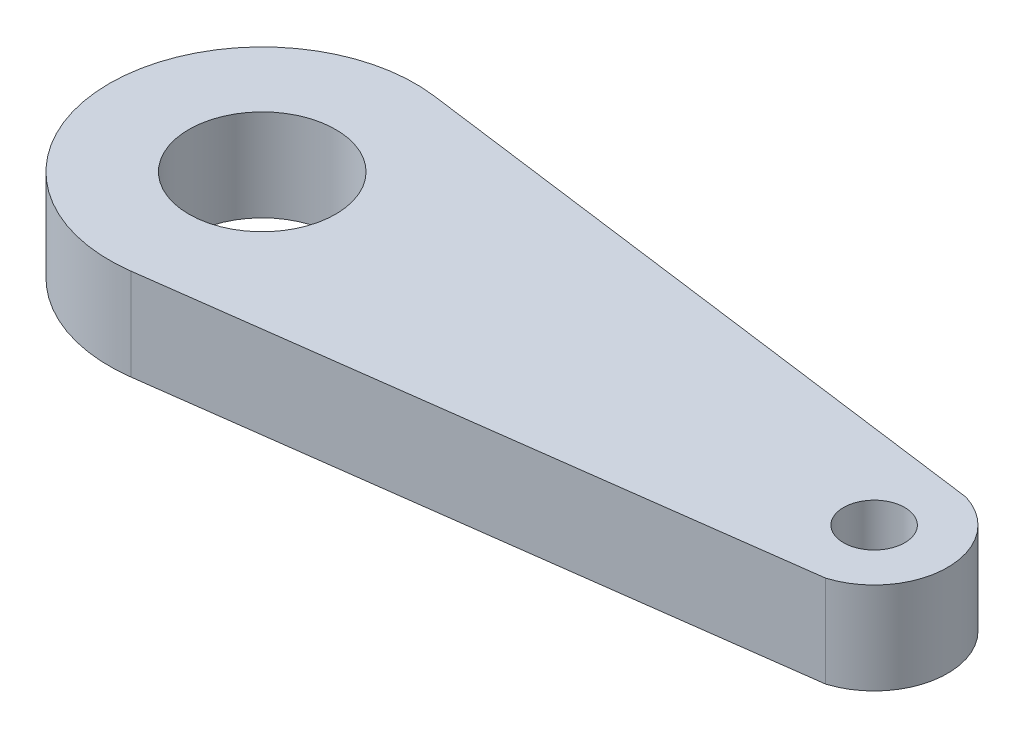
SolidWorks part; units mm, degrees
ref_plane "Front Plane" through (0, 0, 0) normal (0, 0, 1) x (1, 0, 0)
ref_plane "Top Plane" through (0, 0, 0) normal (0, 1, 0) x (1, 0, 0)
ref_plane "Right Plane" through (0, 0, 0) normal (1, 0, 0) x (0, 0, -1)
sketch "Sketch1" plane through (0, 0, 0) normal (0, 1, 0) x (1, 0, 0)
  line L0 (-565.5094, 314.7358) -> (707.5748, 145.6391)
  line L2 (-565.5094, -314.7358) -> (707.5748, -145.6391)
  arc A0 (-565.5094, 314.7358) -> (-565.5094, -314.7358) centre (-607.314, 0) ccw
  arc A1 (657.3717, -152.3073) -> (657.3717, 152.3073) centre (662.686, 0) ccw
  circle A2 centre (-607.314, 0) radius 152.4
  circle A3 centre (662.686, 0) radius 63.5
  dimension "D1" = 635
  dimension "D2" = 304.8
  dimension "D5" = 304.8
  dimension "D6" = 127
  dimension "D3" = 607.314
  dimension "D4" = 1270
extrude "Boss-Extrude1" add sketch "Sketch1" along normal blind 190.5 contours L2 A1 L0 A0 A3 A2
